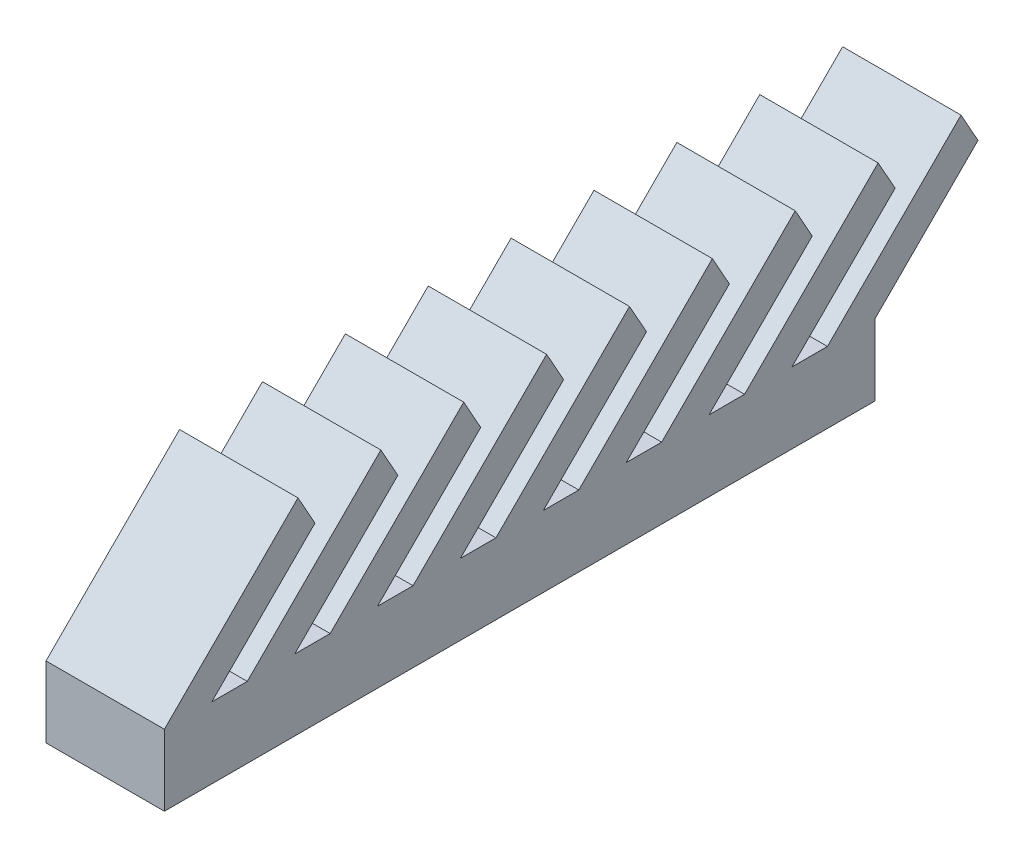
SolidWorks part; units mm, degrees
ref_plane "Front Plane" through (0, 0, 0) normal (0, 0, 1) x (1, 0, 0)
ref_plane "Top Plane" through (0, 0, 0) normal (0, 1, 0) x (1, 0, 0)
ref_plane "Right Plane" through (0, 0, 0) normal (1, 0, 0) x (0, 0, -1)
sketch "Sketch1" plane through (0, 0, 0) normal (1, 0, 0) x (0, 0, -1)
  line L1 (15, -1.5) -> (-15, -1.5)
  line L2 (15, -1.5) -> (15, 1.5)
  line L3 (15, 1.5) -> (-15, 1.5)
  line L4 (-15, -1.5) -> (-15, 1.5)
  line L5 (15, -1.5) -> (-15, 1.5) construction
  line L6 (15, 1.5) -> (-15, -1.5) construction
  point P0 (0, 0)
  dimension "D1" = 3
  dimension "D2" = 30
extrude "Boss-Extrude1" add sketch "Sketch1" along normal blind 5
sketch "Sketch2" plane through (5, 0, 0) normal (1, 0, 0) x (0, 0, -1)
  line L0 (15, 1.5) -> (13, 1.5)
  line L1 (15, 1.5) -> (19.3588, 5.8588)
  line L2 (15, 1.5) -> (-15, 1.5) construction
  line L3 (14, 1.5) -> (19, 1.5) construction
  line L4 (19, 1.5) -> (19, 6.5) construction
  line L5 (14, 1.5) -> (19, 6.5) construction
  line L6 (13, 1.5) -> (18.6412, 7.1412)
  line L7 (19.3588, 5.8588) -> (18.6412, 7.1412)
  point P5 (14, 1.5)
  dimension "D1" = 2
  dimension "D2" = 5
  dimension "D3" = 5
extrude "Boss-Extrude3" add sketch "Sketch2" against normal blind 5
pattern_linear "LPattern2" count 9 spacing 3.5 along (0, 0, 1) of "Boss-Extrude3"
